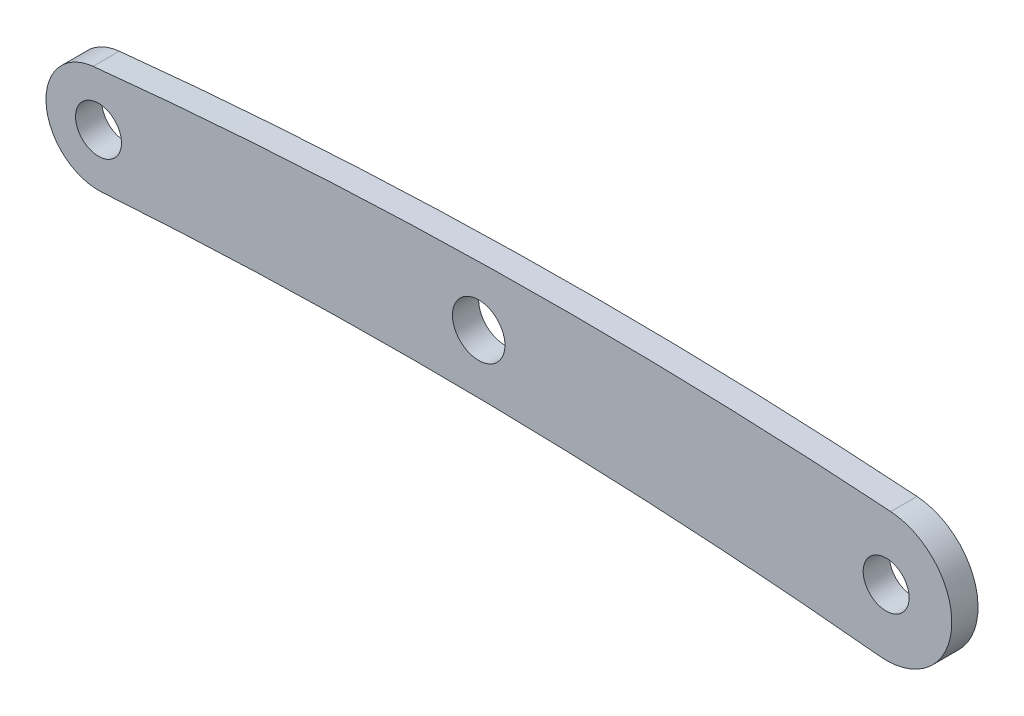
SolidWorks part; units mm, degrees
ref_plane "Front Plane" through (0, 0, 0) normal (0, 0, 1) x (1, 0, 0)
ref_plane "Top Plane" through (0, 0, 0) normal (0, 1, 0) x (1, 0, 0)
ref_plane "Right Plane" through (0, 0, 0) normal (1, 0, 0) x (0, 0, -1)
sketch "Sketch1" plane through (0, 0, 0) normal (0, 0, 1) x (1, 0, 0)
  line L0 (0, 0) -> (60, 0) construction
  circle A0 centre (0, 0) radius 1.75
  arc A1 (-0.4134, 3.9786) -> (0.2722, -3.9907) centre (0, 0) ccw
  circle A2 centre (60, 0) radius 1.75
  arc A3 (59.4942, -4.9744) -> (60.3513, 4.9876) centre (60, 0) ccw
  arc A6 (59.4942, -4.9744) -> (0.2722, -3.9907) centre (24.0917, -353.1793) ccw
  arc A7 (60.3513, 4.9876) -> (-0.4134, 3.9786) centre (35.7583, -344.1473) ccw
  dimension "D2" = 350
  dimension "D3" = 350
  dimension "D5" = 3.5
  dimension "D7" = 8
  dimension "D8" = 10
  dimension "D9" = 3.5
  dimension "D10" = 60
extrude "Boss-Extrude1" add sketch "Sketch1" along normal blind 2
sketch "草图1" plane through (0, 0, 2) normal (0, 0, 1) x (1, 0, 0)
  circle A0 centre (28.9611, 1.2617) radius 2
extrude "切除-拉伸1" cut sketch "草图1" against normal blind 10
